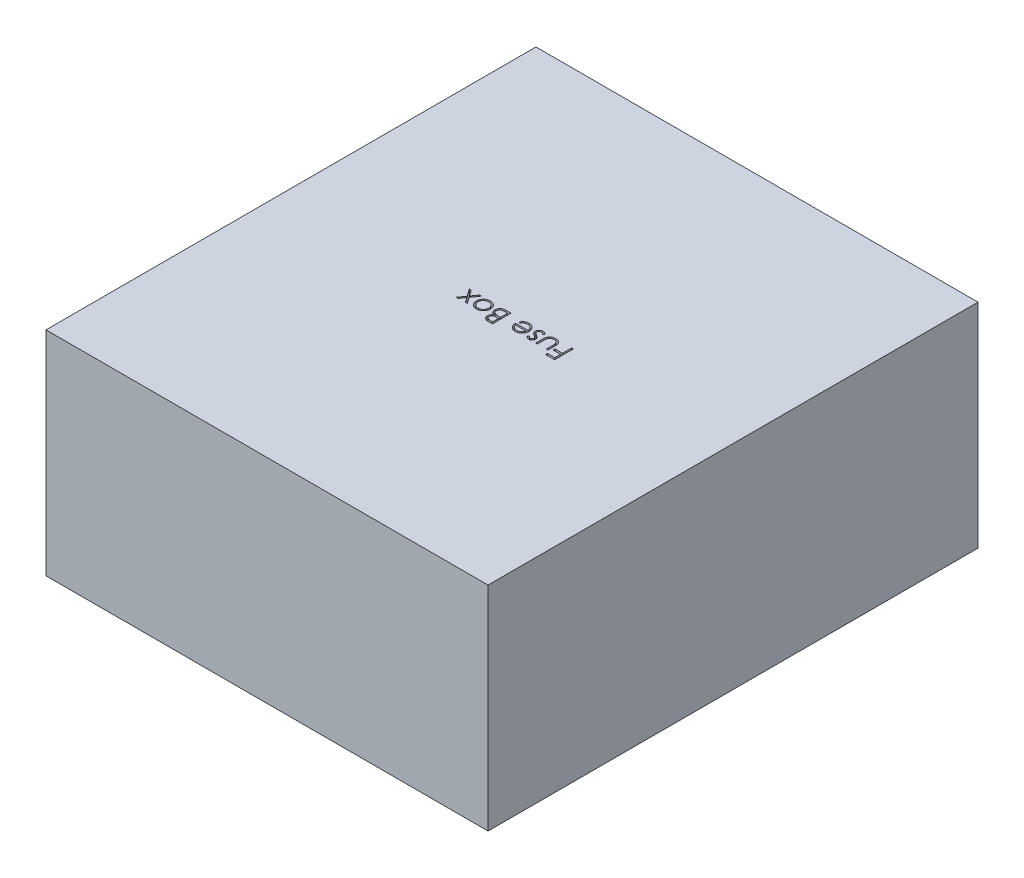
SolidWorks part; units mm, degrees
ref_plane "Front Plane" through (0, 0, 0) normal (0, 0, 1) x (1, 0, 0)
ref_plane "Top Plane" through (0, 0, 0) normal (0, 1, 0) x (1, 0, 0)
ref_plane "Right Plane" through (0, 0, 0) normal (1, 0, 0) x (0, 0, -1)
sketch "Sketch1" plane through (0, 0, 0) normal (0, 1, 0) x (1, 0, 0)
  line L1 (-41.5, -46) -> (41.5, -46)
  line L2 (-41.5, -46) -> (-41.5, 46)
  line L3 (-41.5, 46) -> (41.5, 46)
  line L4 (41.5, -46) -> (41.5, 46)
  line L5 (-41.5, -46) -> (41.5, 46) construction
  line L6 (-41.5, 46) -> (41.5, -46) construction
  point P0 (0, 0)
  dimension "D1" = 92
  dimension "D2" = 83
extrude "Boss-Extrude1" add sketch "Sketch1" along normal blind 40
sketch "Sketch2" plane through (0, 40, 0) normal (0, 1, 0) x (-1, 0, 0)
  text T0 "Fuse Box" font "Century Gothic" height 3.5
extrude "Cut-Extrude1" cut sketch "Sketch2" against normal blind 2
